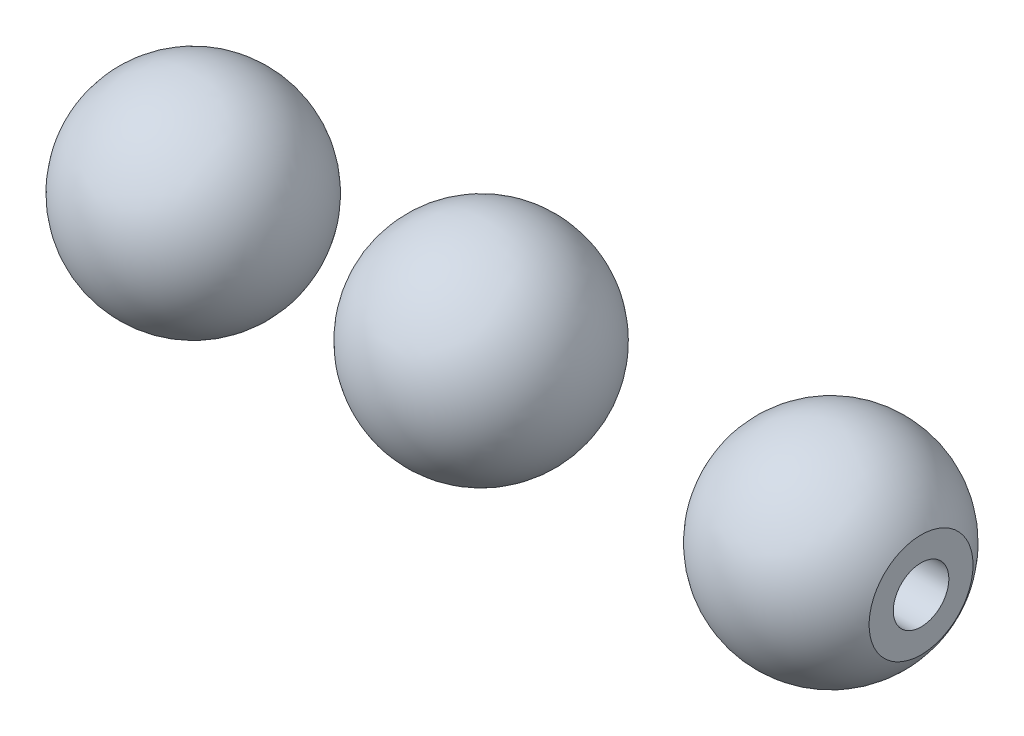
SolidWorks part; units mm, degrees
ref_plane "Front Plane" through (0, 0, 0) normal (0, 0, 1) x (1, 0, 0)
ref_plane "Top Plane" through (0, 0, 0) normal (0, 1, 0) x (1, 0, 0)
ref_plane "Right Plane" through (0, 0, 0) normal (1, 0, 0) x (0, 0, -1)
sketch "Sketch6" plane through (0, 0, 0) normal (1, 0, 0) x (0, 0, -1)
  line L1 (19.5, 0) -> (-22.5, 0)
  line L2 (19.5, 0) -> (19.5, -11.225)
  arc A0 (-22.5, 0) -> (19.5, -11.225) centre (0, 0) ccw
revolve "Revolve7" add sketch "Sketch6" angle 360 about L1
sketch "Sketch7" plane through (0, 0, -19.5) normal (0, 0, -1) x (-1, 0, 0)
  line L0 (0, 0) -> (0, 11.225) construction
  circle A0 centre (0, 0) radius 11.225 construction
sketch "Sketch8" plane through (0, 0, 0) normal (0, 0, 1) x (1, 0, 0)
  line L1 (-81.6747, -3.4911) -> (-39.6747, -3.4911)
  line L2 (-81.6747, 7.7339) -> (-81.6747, -3.4911)
  arc A0 (-39.6747, -3.4911) -> (-81.6747, 7.7339) centre (-62.1747, -3.4911) ccw
  dimension "D1" = 45
revolve "Revolve8" add sketch "Sketch8" angle 360 about L1
sketch "Sketch9" plane through (0, 0, 0) normal (0, 0, 1) x (1, 0, 0)
  line L1 (95.0241, 0) -> (53.0241, 0)
  line L2 (95.0241, 0) -> (95.0241, -11.225)
  arc A0 (53.0241, 0) -> (95.0241, -11.225) centre (75.5241, 0) ccw
revolve "Revolve9" add sketch "Sketch9" angle 360 about L1
sketch "Sketch10" plane through (95.0241, 0, 0) normal (1, 0, 0) x (0, 0, -1)
  line L0 (0, 0) -> (0, 11.225) construction
  circle A0 centre (0, 0) radius 11.225 construction
sketch "Sketch11" plane through (-81.6747, 0, 0) normal (-1, 0, 0) x (0, 0, 1)
  line L0 (0, -3.4911) -> (0, 7.7339) construction
  circle A0 centre (0, -3.4911) radius 11.225 construction
hole_wizard "CBORE for M12 Hex Head Bolt1" positions "3DSketch1" profile "Sketch12" counterbore size "M12" standard "ANSI Metric"
sketch3d "3DSketch1"
  point P0 (-81.6747, -3.4911, 0)
sketch "Sketch12" plane through (-81.6747, -3.4911, 0) normal (0, 1, 0) x (0, 0, 1)
  line L0 (0, 0) -> (0, 35.6052)
  line L1 (0, 35.6052) -> (6, 32)
  line L2 (6, 32) -> (6, 8)
  line L3 (6, 8) -> (10, 8)
  line L4 (10, 8) -> (10, 0)
  line L5 (10, 0) -> (0, 0)
  line L10 (0, 35.6052) -> (-6, 32) construction
  line L11 (0, -6.35) -> (0, 107.95) construction
  dimension "Hole Dia." = 12
  dimension "Hole Depth" = 32
  dimension "C'Bore Dia." = 20
  dimension "C'Bore Depth" = 8
  dimension "Drill Angle" = 118
hole_wizard "CSK for M10 Flat Head Machine Screw1" positions "Sketch13" profile "Sketch14" countersink size "M10" standard "ANSI Metric"
sketch "Sketch13" plane through (0, 0, -19.5) normal (0, 0, -1) x (-1, 0, 0)
  point P0 (0, 0)
sketch "Sketch14" plane through (0, 0, -19.5) normal (1, 0, 0) x (0, 1, 0)
  line L0 (0, 0) -> (0, 37.6052)
  line L1 (0, 37.6052) -> (6, 34)
  line L2 (6, 34) -> (6, 4)
  line L3 (6, 4) -> (10, 0)
  line L5 (10, 0) -> (0, 0)
  line L6 (-6, 4) -> (-10, 0) construction
  line L10 (0, 37.6052) -> (-6, 34) construction
  line L11 (0, -6.35) -> (0, 107.95) construction
  dimension "Hole Dia." = 12
  dimension "Hole Depth" = 34
  dimension "Near C'Sink Dia." = 20
  dimension "Near C'Sink Angle" = 90
  dimension "Drill Angle" = 118
hole_wizard "M12 Clearance Hole1" positions "Sketch15" profile "Sketch16" hole size "M12" standard "ANSI Metric"
sketch "Sketch15" plane through (95.0241, 0, 0) normal (1, 0, 0) x (0, 0, -1)
  point P0 (0, 0)
sketch "Sketch16" plane through (95.0241, 0, 0) normal (0, 1, 0) x (0, 0, -1)
  line L0 (0, 0) -> (0, 37.6052)
  line L1 (0, 37.6052) -> (6, 34)
  line L2 (6, 34) -> (6, 0)
  line L5 (6, 0) -> (0, 0)
  line L10 (0, 37.6052) -> (-6, 34) construction
  line L11 (0, -6.35) -> (0, 107.95) construction
  dimension "Hole Dia." = 12
  dimension "Hole Depth" = 34
  dimension "Drill Angle" = 118
